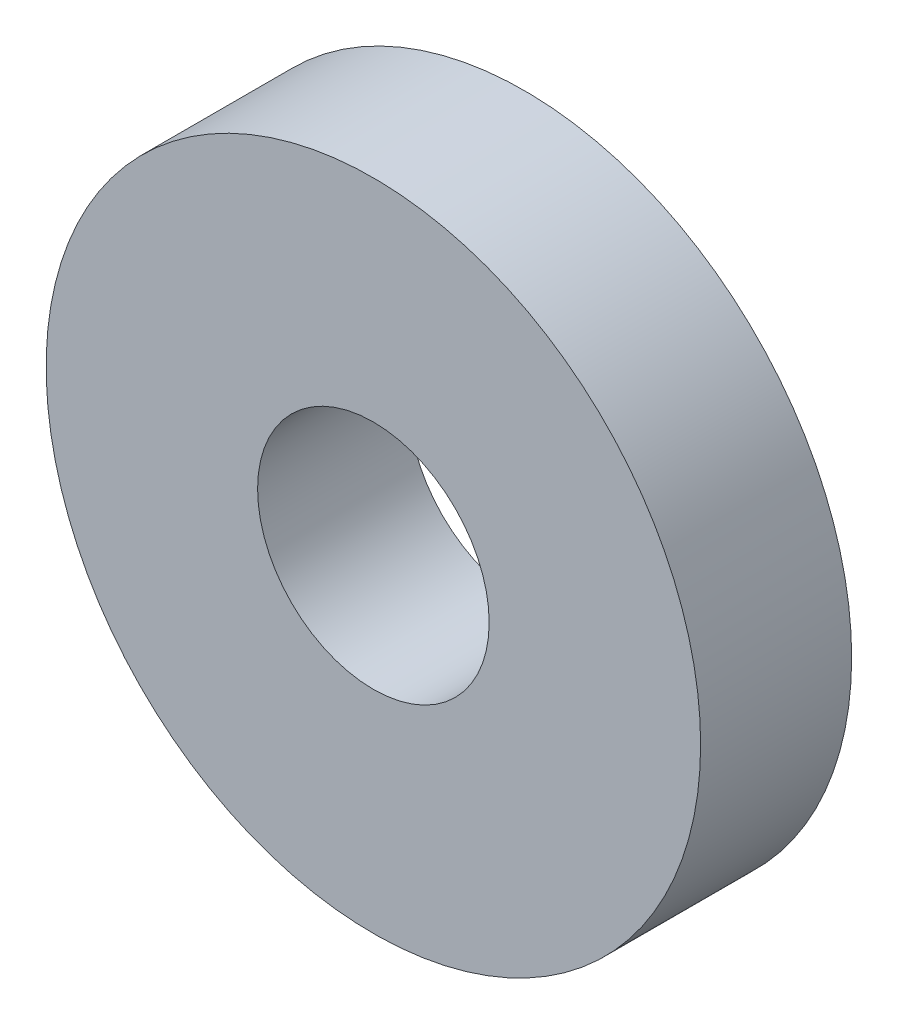
SolidWorks part; units mm, degrees
ref_plane "Front Plane" through (0, 0, 0) normal (0, 0, 1) x (1, 0, 0)
ref_plane "Top Plane" through (0, 0, 0) normal (0, 1, 0) x (1, 0, 0)
ref_plane "Right Plane" through (0, 0, 0) normal (1, 0, 0) x (0, 0, -1)
sketch "Sketch1" plane through (0, 0, 0) normal (0, 0, 1) x (1, 0, 0)
  circle A0 centre (0, 0) radius 9.75
  dimension "D1" = 19.5
extrude "Boss-Extrude1" add sketch "Sketch1" along normal blind 4.5
sketch "Sketch2" plane through (0, 0, 4.5) normal (0, 0, 1) x (1, 0, 0)
  circle A0 centre (0, 0) radius 3.45
  dimension "D1" = 6.9
extrude "Cut-Extrude1" cut sketch "Sketch2" against normal blind 4.5
